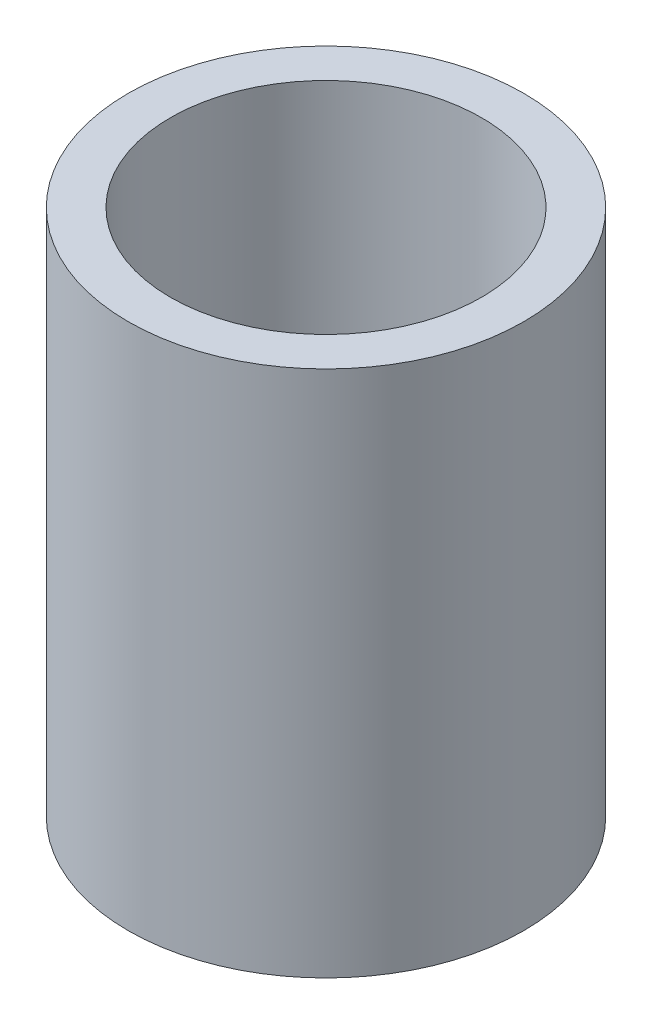
SolidWorks part; units mm, degrees
ref_plane "Front Plane" through (0, 0, 0) normal (0, 0, 1) x (1, 0, 0)
ref_plane "Top Plane" through (0, 0, 0) normal (0, 1, 0) x (1, 0, 0)
ref_plane "Right Plane" through (0, 0, 0) normal (1, 0, 0) x (0, 0, -1)
sketch "Sketch1" plane through (0, 0, 0) normal (0, 1, 0) x (1, 0, 0)
  circle A0 centre (0, 0) radius 1.905
  circle A1 centre (0, 0) radius 1.4986
  dimension "D1" = 3.81
  dimension "D2" = 2.9972
extrude "Boss-Extrude1" add sketch "Sketch1" along normal blind 5.08
